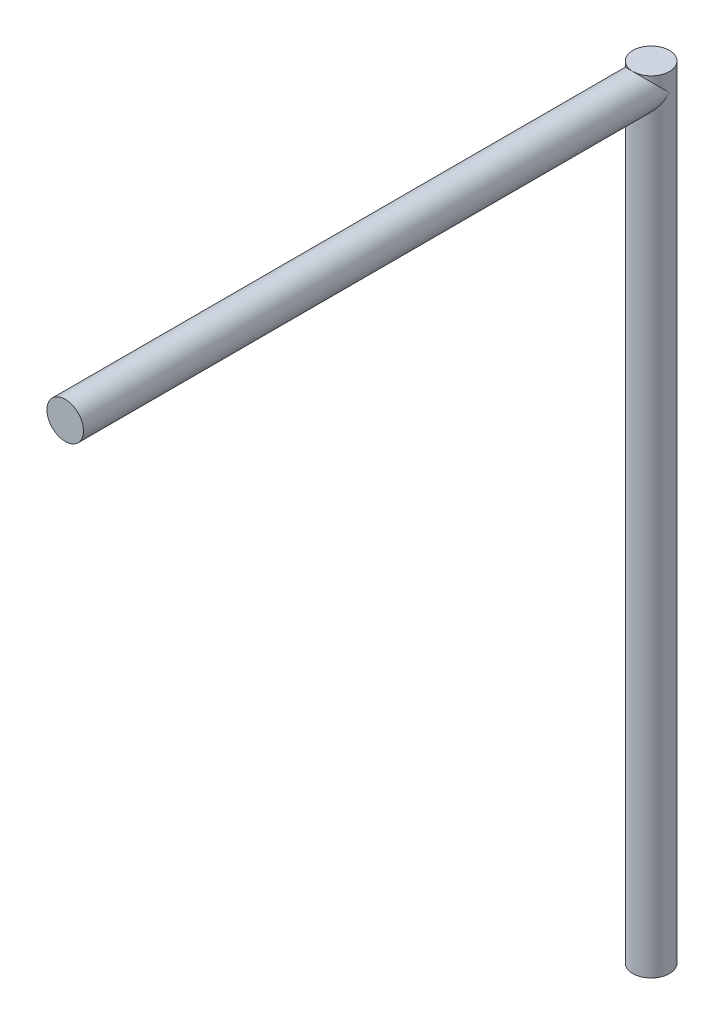
SolidWorks part; units mm, degrees
material "AISI 1015 Steel, Cold Drawn (SS)"
ref_plane "Front Plane" through (0, 0, 0) normal (0, 0, 1) x (1, 0, 0)
ref_plane "Top Plane" through (0, 0, 0) normal (0, 1, 0) x (1, 0, 0)
ref_plane "Right Plane" through (0, 0, 0) normal (1, 0, 0) x (0, 0, -1)
sketch "Sketch1" plane through (0, 0, 0) normal (0, 1, 0) x (1, 0, 0)
  circle A0 centre (0, 0) radius 4.7625
  dimension "D1" = 9.525
extrude "Boss-Extrude1" add sketch "Sketch1" along normal blind 203.2
sketch "Sketch2" plane through (0, 0, 0) normal (0, 0, 1) x (1, 0, 0)
  line L0 (4.7625, 0) -> (4.7625, 203.2) construction
  line L1 (4.7625, 203.2) -> (-4.7625, 203.2) construction
  line L2 (-4.7625, 203.2) -> (-4.7625, 0) construction
  circle A0 centre (0, 198.4375) radius 4.7625
extrude "Boss-Extrude2" add sketch "Sketch2" along normal blind 152.4
